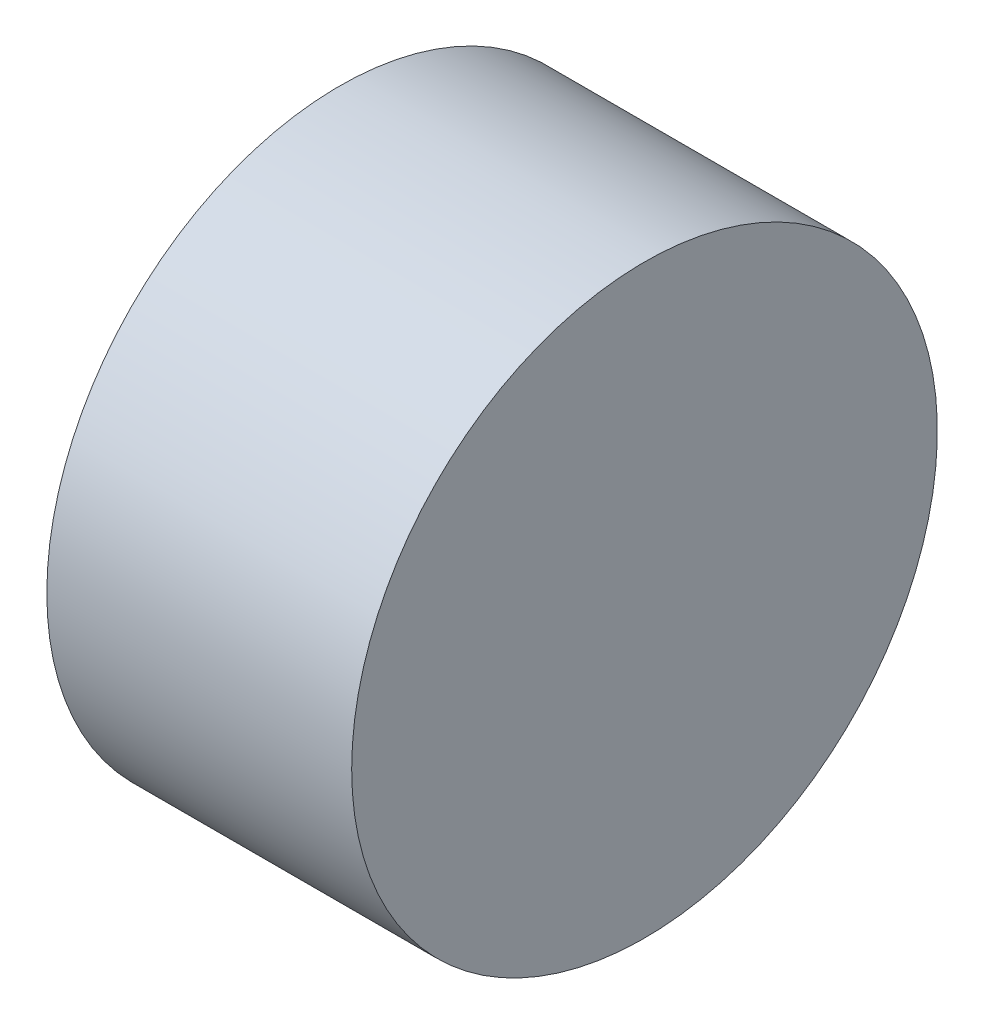
SolidWorks part; units mm, degrees
ref_plane "前视基准面" through (0, 0, 0) normal (0, 0, 1) x (1, 0, 0)
ref_plane "上视基准面" through (0, 0, 0) normal (0, 1, 0) x (1, 0, 0)
ref_plane "右视基准面" through (0, 0, 0) normal (1, 0, 0) x (0, 0, -1)
sketch "草图1" plane through (0, 0, 0) normal (0, 1, 0) x (1, 0, 0)
  line L0 (-159.6132, 0) -> (7821.0463, 0) construction
  line L1 (0, -159.6132) -> (0, 7821.0463) construction
  line L2 (0, 0) -> (-16.7, 0)
  line L3 (-16.7, 0) -> (-16.7, 3)
  line L4 (-16.7, 3) -> (-12.7, 3)
  line L5 (-12.7, 3) -> (-12.7, 12.2)
  line L6 (-12.7, 12.2) -> (0, 12.2)
  line L7 (0, 12.2) -> (0, 0)
  point P4 (-16.7, 0)
  dimension "D1" = 16.7
  dimension "D2" = 3
  dimension "D3" = 4
  dimension "D4" = 9.2
revolve "旋转1" add sketch "草图1" angle 360 about L0
sketch "草图3" plane through (-12.7, 0, 0) normal (-1, 0, 0) x (0, 0, 1)
  arc A0 (-8.668, 2.4219) -> (-8.8544, -1.6122) centre (0, 0) ccw
  arc A1 (-10.5942, 2.9601) -> (-10.8221, -1.9705) centre (0, 0) ccw
  arc A2 (-8.668, 2.4219) -> (-10.5942, 2.9601) centre (-9.9002, 1.7279) ccw
  arc A3 (-8.8544, -1.6122) -> (-10.8221, -1.9705) centre (-10.0174, -0.8075) cw
  arc A4 (6.4315, 6.2957) -> (3.031, 8.4743) centre (0, 0) ccw
  arc A5 (6.4315, 6.2957) -> (7.8607, 7.6948) centre (6.4465, 7.7099) ccw
  arc A6 (7.8607, 7.6948) -> (3.7045, 10.3574) centre (0, 0) ccw
  arc A7 (3.031, 8.4743) -> (3.7045, 10.3574) centre (4.3093, 9.0791) cw
  arc A8 (2.2365, -8.7177) -> (5.8234, -6.862) centre (0, 0) ccw
  arc A9 (2.2365, -8.7177) -> (2.7335, -10.6549) centre (3.4537, -9.4378) ccw
  arc A10 (2.7335, -10.6549) -> (7.1175, -8.3869) centre (0, 0) ccw
  arc A11 (5.8234, -6.862) -> (7.1175, -8.3869) centre (5.708, -8.2715) cw
  point P11 (-10.5942, 2.9601)
  point P12 (-10.8221, -1.9705)
  point P13 (-8.8544, -1.6122)
  point P14 (-8.668, 2.4219)
  point P27 (0, 0)
  dimension "D1" = 18
  dimension "D2" = 22
  dimension "D3" = 1.4142
  dimension "D4" = 3
extrude "切除-拉伸1" cut sketch "草图3" against normal blind 3
sketch "草图4" plane through (-12.7, 0, 0) normal (-1, 0, 0) x (0, 0, 1)
  line L0 (-8.668, 2.4219) -> (3.031, 8.4743) construction
  line L1 (0, 0) -> (-22974.5091, 44409.1424) construction
  point P3 (-8.668, 2.4219)
  point P4 (3.031, 8.4743)
  point P9 (-2.8185, 5.4481)
  point P12 (-4.1354, 7.9936)
  point P27 (0, 0)
  circle B0 centre (-2.8185, 5.4481) radius 0.75
  circle B1 centre (-4.1354, 7.9936) radius 0.75
  circle B2 centre (8.9904, -0.4155) radius 0.75
  circle B3 centre (6.1274, -0.2832) radius 0.75
  circle B4 centre (-4.855, -7.5782) radius 0.75
  circle B5 centre (-3.3089, -5.1649) radius 0.75
sketch_block_instance "块1-1"
sketch_block "块1" parameters "D1"=1.5, "D2"=1.5
extrude "切除-拉伸2" cut sketch "草图4" against normal blind 3
sketch "草图6" plane through (-12.7, 0, 0) normal (-1, 0, 0) x (0, 0, 1)
  line L0 (0, -1000) -> (0, 49000) construction
  point P1 (0, 5.0835)
  point P4 (0, -5.0835)
  point P7 (0, 0)
  circle B0 centre (0, 5.0835) radius 0.65
  circle B1 centre (0, -5.0835) radius 0.65
  dimension "D1" = 2
sketch_block_instance "块2-1"
sketch_block "块2" parameters "D1"=1.3, "D2"=1.3
extrude "切除-拉伸3" cut sketch "草图6" against normal blind 3
